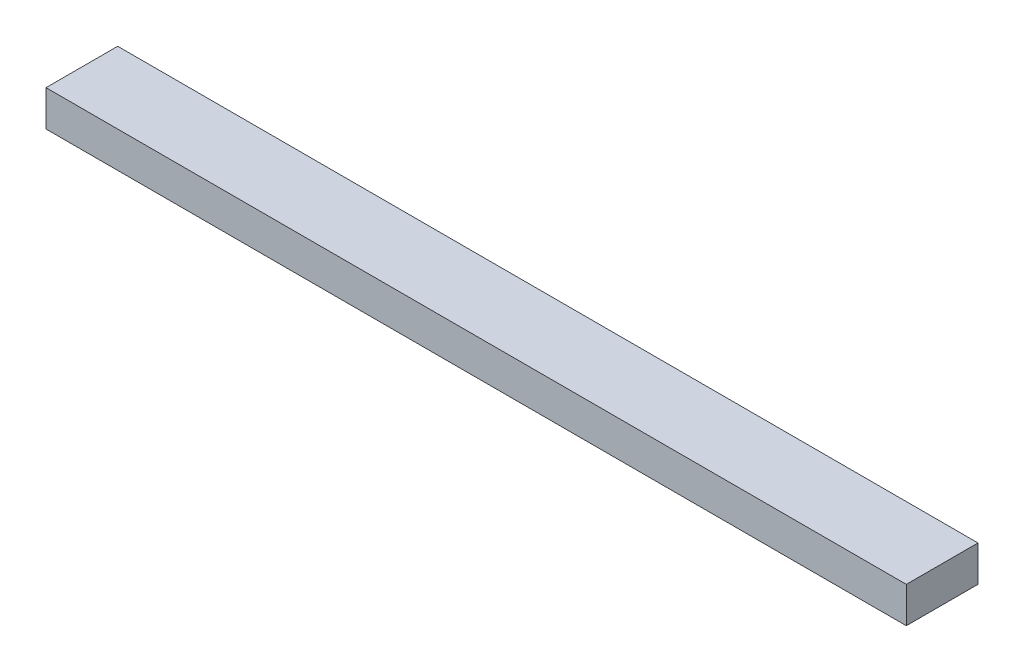
SolidWorks part; units mm, degrees
ref_plane "Front Plane" through (0, 0, 0) normal (0, 0, 1) x (1, 0, 0)
ref_plane "Top Plane" through (0, 0, 0) normal (0, 1, 0) x (1, 0, 0)
ref_plane "Right Plane" through (0, 0, 0) normal (1, 0, 0) x (0, 0, -1)
sketch "Sketch1" plane through (0, 0, 0) normal (1, 0, 0) x (0, 0, -1)
  line L1 (-50.8, -25.4) -> (50.8, -25.4)
  line L2 (-50.8, -25.4) -> (-50.8, 25.4)
  line L3 (-50.8, 25.4) -> (50.8, 25.4)
  line L4 (50.8, -25.4) -> (50.8, 25.4)
  line L5 (-50.8, -25.4) -> (50.8, 25.4) construction
  line L6 (-50.8, 25.4) -> (50.8, -25.4) construction
  point P0 (0, 0)
  dimension "D1" = 101.6
  dimension "D2" = 50.8
extrude "Boss-Extrude1" add sketch "Sketch1" along normal blind 1219.2
equation "\"Length\"=48"
equation "\"D1@Boss-Extrude1\"=\"Length\""
